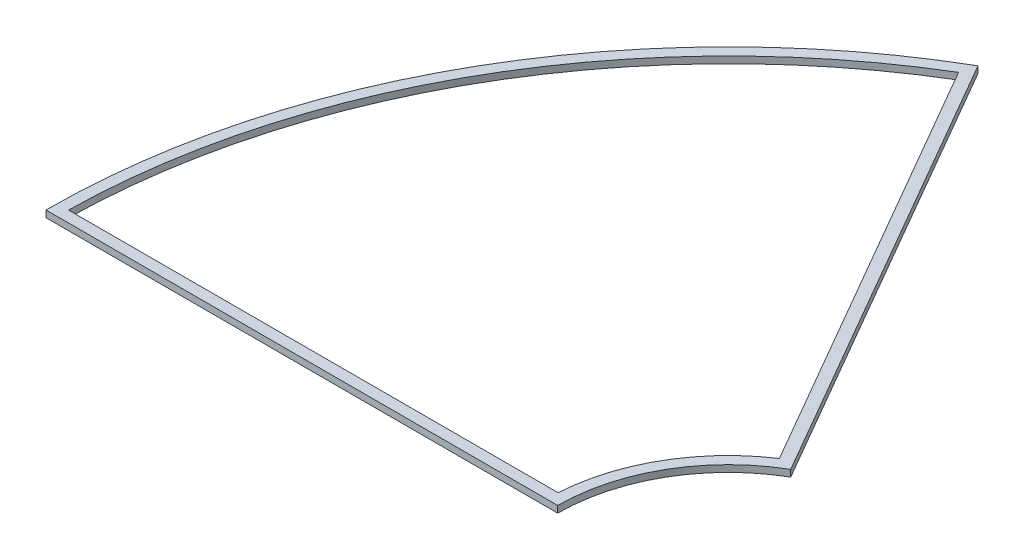
SolidWorks part; units mm, degrees
ref_plane "Front Plane" through (0, 0, 0) normal (0, 0, 1) x (1, 0, 0)
ref_plane "Top Plane" through (0, 0, 0) normal (0, 1, 0) x (1, 0, 0)
ref_plane "Right Plane" through (0, 0, 0) normal (1, 0, 0) x (0, 0, -1)
sketch "Sketch1" plane through (0, 0, 0) normal (0, 1, 0) x (1, 0, 0)
  line L0 (-152.4, 0) -> (-609.6, 0)
  line L1 (-76.2, 131.9823) -> (-304.8, 527.9291)
  line L2 (-530.4113, 300.4596) -> (-530.4291, 300.4699)
  line L3 (-525.4113, 309.1199) -> (-525.4291, 309.1301)
  line L5 (-89.7062, 135.3756) -> (-171.2603, 276.6315)
  line L6 (-162.0918, 10) -> (-325.2, 10)
  line L7 (-176.2603, 285.2917) -> (-308.4186, 514.1966)
  line L10 (-335.2, 10) -> (-599.5166, 10)
  line L14 (-89.7062, 135.3756) -> (-308.4186, 514.1966) construction
  line L15 (-176.2603, 285.2917) -> (-171.2603, 276.6315)
  line L16 (-162.0918, 10) -> (-599.5166, 10) construction
  line L17 (-335.2, 10) -> (-325.2, 10)
  arc A0 (-609.6, 0) -> (-304.8, 527.9291) centre (0, 0) cw
  arc A1 (-76.2, 131.9823) -> (-152.4, 0) centre (0, 0) ccw
  arc A2 (-599.5166, 10) -> (-521.7508, 295.4594) centre (0, 0) cw
  arc A3 (-89.7062, 135.3756) -> (-162.0918, 10) centre (0, 0) ccw
  arc A4 (-516.7508, 304.1197) -> (-308.4186, 514.1966) centre (0, 0) cw
  arc A5 (-521.7508, 295.4594) -> (-516.7508, 304.1197) centre (0, 0) cw
  arc A6 (-599.5166, 10) -> (-308.4186, 514.1966) centre (0, 0) cw construction
  point P5 (-330.2, 0)
  point P7 (0, 0)
  point P9 (-165.1, 285.9616)
  dimension "D3" = 330.2
  dimension "D1" = 609.6
  dimension "D4" = 330.2
  dimension "D5" = 10
  dimension "D2" = 2
extrude "Boss-Extrude1" add sketch "Sketch1" along normal blind 6 contours A1 L1 A0 L0 A2 A5 A4 L7 L15 L5 A3 L6 L17 L10
